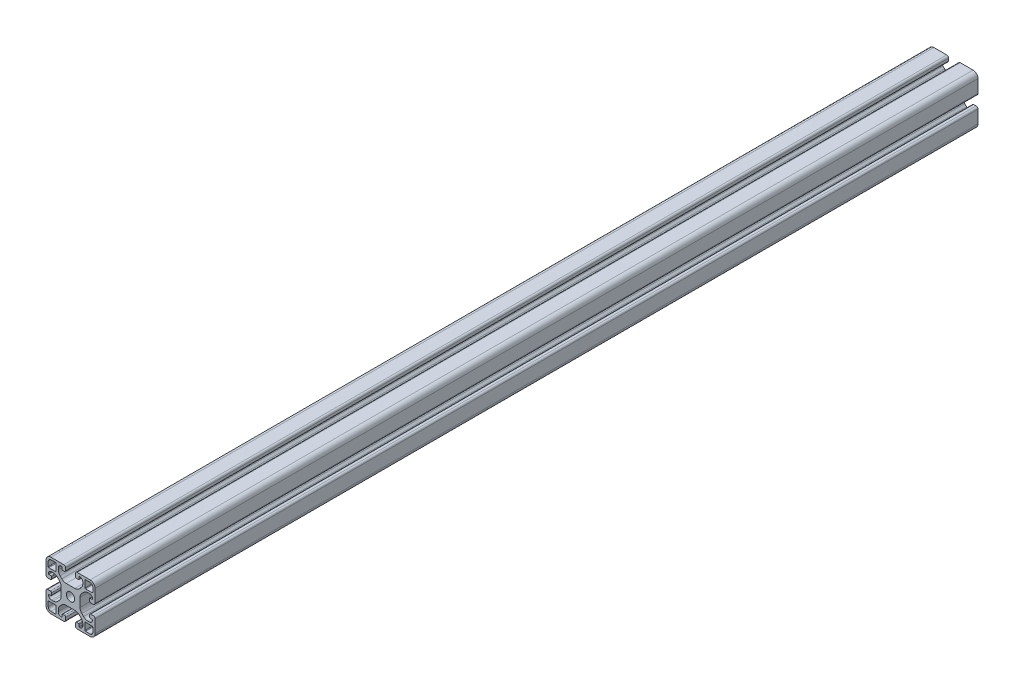
SolidWorks part; units mm, degrees
ref_plane "Plan de face" through (0, 0, 0) normal (0, 0, 1) x (1, 0, 0)
ref_plane "Plan de dessus" through (0, 0, 0) normal (0, 1, 0) x (1, 0, 0)
ref_plane "Plan de droite" through (0, 0, 0) normal (1, 0, 0) x (0, 0, -1)
ref_plane "Plan1" through (0, 0, -30) normal (0, 0, -1) x (-1, 0, 0)
sketch "Esquisse1" plane through (0, 0, -30) normal (0, 0, -1) x (-1, 0, 0)
  line L0 (-4.5, 15) -> (-4.5, 13.5)
  line L1 (-4, 13) -> (-2.5, 13)
  line L2 (-4.5, 10) -> (-5.8076, 10)
  line L3 (-9.3431, 11.4645) -> (-10.7855, 12.9069)
  line L4 (-12.25, 16.4424) -> (-12.25, 23.5576)
  line L5 (-10.7855, 27.0931) -> (-9.3431, 28.5355)
  line L6 (-5.8076, 30) -> (-4.5, 30)
  line L7 (-2.5, 27) -> (-4, 27)
  line L8 (-4.5, 26.5) -> (-4.5, 25)
  line L9 (-3.5, 24) -> (-1.5, 24)
  line L10 (0, 25.5) -> (0, 36)
  line L11 (-4, 40) -> (-14.5, 40)
  line L12 (-16, 38.5) -> (-16, 36.5)
  line L13 (-15, 35.5) -> (-13.5, 35.5)
  line L14 (-13, 36) -> (-13, 37.5)
  line L15 (-10, 35.5) -> (-10, 34.1924)
  line L16 (-11.4645, 30.6569) -> (-12.9069, 29.2145)
  line L17 (-16.4424, 27.75) -> (-23.5576, 27.75)
  line L18 (-27.0931, 29.2145) -> (-28.5355, 30.6569)
  line L19 (-30, 34.1924) -> (-30, 35.5)
  line L20 (-27, 37.5) -> (-27, 36)
  line L21 (-26.5, 35.5) -> (-25, 35.5)
  line L22 (-24, 36.5) -> (-24, 38.5)
  line L23 (-25.5, 40) -> (-36, 40)
  line L24 (-40, 36) -> (-40, 25.5)
  line L25 (-38.5, 24) -> (-36.5, 24)
  line L26 (-35.5, 25) -> (-35.5, 26.5)
  line L27 (-36, 27) -> (-37.5, 27)
  line L28 (-35.5, 30) -> (-34.1924, 30)
  line L29 (-30.6569, 28.5355) -> (-29.2145, 27.0931)
  line L30 (-27.75, 23.5576) -> (-27.75, 16.4424)
  line L31 (-29.2145, 12.9069) -> (-30.6569, 11.4645)
  line L32 (-34.1924, 10) -> (-35.5, 10)
  line L33 (-37.5, 13) -> (-36, 13)
  line L34 (-35.5, 13.5) -> (-35.5, 15)
  line L35 (-36.5, 16) -> (-38.5, 16)
  line L36 (-40, 14.5) -> (-40, 4)
  line L37 (-36, 0) -> (-25.5, 0)
  line L38 (-24, 1.5) -> (-24, 3.5)
  line L39 (-25, 4.5) -> (-26.5, 4.5)
  line L40 (-27, 4) -> (-27, 2.5)
  line L41 (-30, 4.5) -> (-30, 5.8076)
  line L42 (-28.5355, 9.3431) -> (-27.0931, 10.7855)
  line L43 (-23.5576, 12.25) -> (-16.4424, 12.25)
  line L44 (-12.9069, 10.7855) -> (-11.4645, 9.3431)
  line L45 (-10, 5.8076) -> (-10, 4.5)
  line L46 (-13, 2.5) -> (-13, 4)
  line L47 (-13.5, 4.5) -> (-15, 4.5)
  line L48 (-16, 3.5) -> (-16, 1.5)
  line L49 (-14.5, 0) -> (-4, 0)
  line L50 (0, 4) -> (0, 14.5)
  line L51 (-1.5, 16) -> (-3.5, 16)
  line L52 (-4, 1.8) -> (-7.7, 1.8)
  line L53 (-8.2, 2.3) -> (-8.2, 7.7)
  line L54 (-7.7, 8.2) -> (-2.3, 8.2)
  line L55 (-1.8, 7.7) -> (-1.8, 4)
  line L56 (-38.2, 4) -> (-38.2, 7.7)
  line L57 (-37.7, 8.2) -> (-32.3, 8.2)
  line L58 (-31.8, 7.7) -> (-31.8, 2.3)
  line L59 (-32.3, 1.8) -> (-36, 1.8)
  line L60 (-36, 38.2) -> (-32.3, 38.2)
  line L61 (-31.8, 37.7) -> (-31.8, 32.3)
  line L62 (-32.3, 31.8) -> (-37.7, 31.8)
  line L63 (-38.2, 32.3) -> (-38.2, 36)
  line L64 (-1.8, 36) -> (-1.8, 32.3)
  line L65 (-2.3, 31.8) -> (-7.7, 31.8)
  line L66 (-8.2, 32.3) -> (-8.2, 37.7)
  line L67 (-7.7, 38.2) -> (-4, 38.2)
  arc A0 (-4.5, 13.5) -> (-4, 13) centre (-4, 13.5) ccw
  arc A1 (-2.5, 13) -> (-2, 12.5) centre (-2.5, 12.5) cw
  arc A2 (-2, 12.5) -> (-4.5, 10) centre (-4.5, 12.5) cw
  arc A3 (-5.8076, 10) -> (-9.3431, 11.4645) centre (-5.8076, 15) cw
  arc A4 (-10.7855, 12.9069) -> (-12.25, 16.4424) centre (-7.25, 16.4424) cw
  arc A5 (-12.25, 23.5576) -> (-10.7855, 27.0931) centre (-7.25, 23.5576) cw
  arc A6 (-9.3431, 28.5355) -> (-5.8076, 30) centre (-5.8076, 25) cw
  arc A7 (-4.5, 30) -> (-2, 27.5) centre (-4.5, 27.5) cw
  arc A8 (-2, 27.5) -> (-2.5, 27) centre (-2.5, 27.5) cw
  arc A9 (-4, 27) -> (-4.5, 26.5) centre (-4, 26.5) ccw
  arc A10 (-4.5, 25) -> (-3.5, 24) centre (-3.5, 25) ccw
  arc A11 (-1.5, 24) -> (0, 25.5) centre (-1.5, 25.5) ccw
  arc A12 (0, 36) -> (-4, 40) centre (-4, 36) ccw
  arc A13 (-14.5, 40) -> (-16, 38.5) centre (-14.5, 38.5) ccw
  arc A14 (-16, 36.5) -> (-15, 35.5) centre (-15, 36.5) ccw
  arc A15 (-13.5, 35.5) -> (-13, 36) centre (-13.5, 36) ccw
  arc A16 (-13, 37.5) -> (-12.5, 38) centre (-12.5, 37.5) cw
  arc A17 (-12.5, 38) -> (-10, 35.5) centre (-12.5, 35.5) cw
  arc A18 (-10, 34.1924) -> (-11.4645, 30.6569) centre (-15, 34.1924) cw
  arc A19 (-12.9069, 29.2145) -> (-16.4424, 27.75) centre (-16.4424, 32.75) cw
  arc A20 (-23.5576, 27.75) -> (-27.0931, 29.2145) centre (-23.5576, 32.75) cw
  arc A21 (-28.5355, 30.6569) -> (-30, 34.1924) centre (-25, 34.1924) cw
  arc A22 (-30, 35.5) -> (-27.5, 38) centre (-27.5, 35.5) cw
  arc A23 (-27.5, 38) -> (-27, 37.5) centre (-27.5, 37.5) cw
  arc A24 (-27, 36) -> (-26.5, 35.5) centre (-26.5, 36) ccw
  arc A25 (-25, 35.5) -> (-24, 36.5) centre (-25, 36.5) ccw
  arc A26 (-24, 38.5) -> (-25.5, 40) centre (-25.5, 38.5) ccw
  arc A27 (-36, 40) -> (-40, 36) centre (-36, 36) ccw
  arc A28 (-40, 25.5) -> (-38.5, 24) centre (-38.5, 25.5) ccw
  arc A29 (-36.5, 24) -> (-35.5, 25) centre (-36.5, 25) ccw
  arc A30 (-35.5, 26.5) -> (-36, 27) centre (-36, 26.5) ccw
  arc A31 (-37.5, 27) -> (-38, 27.5) centre (-37.5, 27.5) cw
  arc A32 (-38, 27.5) -> (-35.5, 30) centre (-35.5, 27.5) cw
  arc A33 (-34.1924, 30) -> (-30.6569, 28.5355) centre (-34.1924, 25) cw
  arc A34 (-29.2145, 27.0931) -> (-27.75, 23.5576) centre (-32.75, 23.5576) cw
  arc A35 (-27.75, 16.4424) -> (-29.2145, 12.9069) centre (-32.75, 16.4424) cw
  arc A36 (-30.6569, 11.4645) -> (-34.1924, 10) centre (-34.1924, 15) cw
  arc A37 (-35.5, 10) -> (-38, 12.5) centre (-35.5, 12.5) cw
  arc A38 (-38, 12.5) -> (-37.5, 13) centre (-37.5, 12.5) cw
  arc A39 (-36, 13) -> (-35.5, 13.5) centre (-36, 13.5) ccw
  arc A40 (-35.5, 15) -> (-36.5, 16) centre (-36.5, 15) ccw
  arc A41 (-38.5, 16) -> (-40, 14.5) centre (-38.5, 14.5) ccw
  arc A42 (-40, 4) -> (-36, 0) centre (-36, 4) ccw
  arc A43 (-25.5, 0) -> (-24, 1.5) centre (-25.5, 1.5) ccw
  arc A44 (-24, 3.5) -> (-25, 4.5) centre (-25, 3.5) ccw
  arc A45 (-26.5, 4.5) -> (-27, 4) centre (-26.5, 4) ccw
  arc A46 (-27, 2.5) -> (-27.5, 2) centre (-27.5, 2.5) cw
  arc A47 (-27.5, 2) -> (-30, 4.5) centre (-27.5, 4.5) cw
  arc A48 (-30, 5.8076) -> (-28.5355, 9.3431) centre (-25, 5.8076) cw
  arc A49 (-27.0931, 10.7855) -> (-23.5576, 12.25) centre (-23.5576, 7.25) cw
  arc A50 (-16.4424, 12.25) -> (-12.9069, 10.7855) centre (-16.4424, 7.25) cw
  arc A51 (-11.4645, 9.3431) -> (-10, 5.8076) centre (-15, 5.8076) cw
  arc A52 (-10, 4.5) -> (-12.5, 2) centre (-12.5, 4.5) cw
  arc A53 (-12.5, 2) -> (-13, 2.5) centre (-12.5, 2.5) cw
  arc A54 (-13, 4) -> (-13.5, 4.5) centre (-13.5, 4) ccw
  arc A55 (-15, 4.5) -> (-16, 3.5) centre (-15, 3.5) ccw
  arc A56 (-16, 1.5) -> (-14.5, 0) centre (-14.5, 1.5) ccw
  arc A57 (-4, 0) -> (0, 4) centre (-4, 4) ccw
  arc A58 (0, 14.5) -> (-1.5, 16) centre (-1.5, 14.5) ccw
  arc A59 (-3.5, 16) -> (-4.5, 15) centre (-3.5, 15) ccw
  circle A60 centre (-20, 20) radius 3.4
  arc A61 (-1.8, 4) -> (-4, 1.8) centre (-4, 4) cw
  arc A62 (-7.7, 1.8) -> (-8.2, 2.3) centre (-7.7, 2.3) cw
  arc A63 (-8.2, 7.7) -> (-7.7, 8.2) centre (-7.7, 7.7) cw
  arc A64 (-2.3, 8.2) -> (-1.8, 7.7) centre (-2.3, 7.7) cw
  arc A65 (-36, 1.8) -> (-38.2, 4) centre (-36, 4) cw
  arc A66 (-38.2, 7.7) -> (-37.7, 8.2) centre (-37.7, 7.7) cw
  arc A67 (-32.3, 8.2) -> (-31.8, 7.7) centre (-32.3, 7.7) cw
  arc A68 (-31.8, 2.3) -> (-32.3, 1.8) centre (-32.3, 2.3) cw
  arc A69 (-38.2, 36) -> (-36, 38.2) centre (-36, 36) cw
  arc A70 (-32.3, 38.2) -> (-31.8, 37.7) centre (-32.3, 37.7) cw
  arc A71 (-31.8, 32.3) -> (-32.3, 31.8) centre (-32.3, 32.3) cw
  arc A72 (-37.7, 31.8) -> (-38.2, 32.3) centre (-37.7, 32.3) cw
  arc A73 (-4, 38.2) -> (-1.8, 36) centre (-4, 36) cw
  arc A74 (-1.8, 32.3) -> (-2.3, 31.8) centre (-2.3, 32.3) cw
  arc A75 (-7.7, 31.8) -> (-8.2, 32.3) centre (-7.7, 32.3) cw
  arc A76 (-8.2, 37.7) -> (-7.7, 38.2) centre (-7.7, 37.7) cw
extrude "Boss.-Extru.1" add sketch "Esquisse1" against normal blind 720
